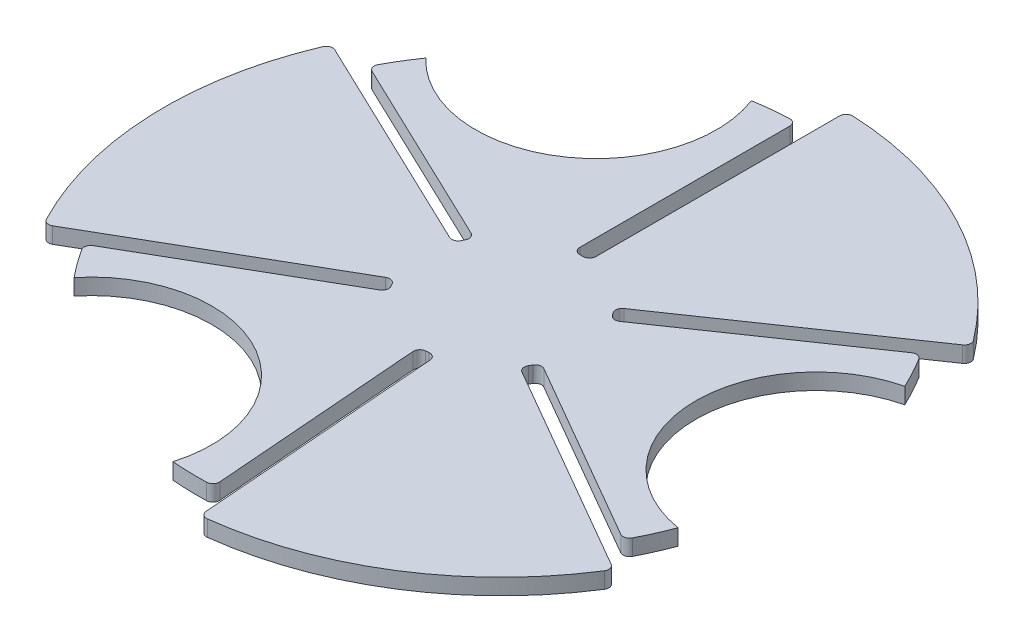
SolidWorks part; units mm, degrees
ref_plane "前基準面" through (0, 0, 0) normal (0, 0, 1) x (1, 0, 0)
ref_plane "上基準面" through (0, 0, 0) normal (0, 1, 0) x (1, 0, 0)
ref_plane "右基準面" through (0, 0, 0) normal (1, 0, 0) x (0, 0, -1)
sketch "草圖1" plane through (0, 0, 0) normal (0, 1, 0) x (1, 0, 0)
  line L2 (50.5659, -26.3075) -> (22.9006, -10.3349)
  line L8 (-2.5, 56.9451) -> (-2.5, 25)
  line L9 (-2.5, 25) -> (2.5, 25)
  line L10 (2.5, 56.9451) -> (2.5, 25)
  line L11 (22.9006, -10.3349) -> (20.4006, -14.6651)
  line L12 (48.0659, -30.6376) -> (20.4006, -14.6651)
  line L13 (-48.0659, -30.6376) -> (-20.4006, -14.6651)
  line L14 (-20.4006, -14.6651) -> (-22.9006, -10.3349)
  line L15 (-50.5659, -26.3075) -> (-22.9006, -10.3349)
  line L16 (20.6126, 14.1465) -> (0, 0) construction
  line L17 (4.4373, -24.7297) -> (6.9225, -56.5781)
  line L18 (22.0272, 12.0852) -> (48.3661, 30.1616)
  line L19 (19.1979, 16.2077) -> (45.5368, 34.2841)
  line L20 (19.1979, 16.2077) -> (22.0272, 12.0852)
  line L21 (-0.5475, -25.1187) -> (1.9377, -56.9671)
  line L22 (4.4373, -24.7297) -> (-0.5475, -25.1187)
  line L23 (-23.6352, 8.522) -> (-52.4593, 22.2939)
  line L24 (-21.4797, 13.0335) -> (-50.3038, 26.8054)
  line L25 (-23.6352, 8.522) -> (-21.4797, 13.0335)
  arc A35 (-2.5, 56.9451) -> (-50.3038, 26.8054) centre (0, 0) ccw
  circle A36 centre (0, 0) radius 25 construction
  arc A37 (50.5659, -26.3075) -> (48.3661, 30.1616) centre (0, 0) ccw
  arc A38 (-48.0659, -30.6376) -> (1.9377, -56.9671) centre (0, 0) ccw
  arc A39 (45.5368, 34.2841) -> (2.5, 56.9451) centre (0, 0) ccw
  arc A40 (-52.4593, 22.2939) -> (-50.5659, -26.3075) centre (0, 0) ccw
  arc A41 (6.9225, -56.5781) -> (48.0659, -30.6376) centre (0, 0) ccw
  point P1 (0, 25)
  dimension "D1" = 114
  dimension "D2" = 5
  dimension "D3" = 50
  dimension "D4" = 55.538
  dimension "D5" = 3
extrude "填料-伸長1" add sketch "草圖1" against normal blind 5
sketch "草圖4" plane through (0, 0, 0) normal (0, 1, 0) x (1, 0, 0)
  line L0 (48.0659, -30.6376) -> (20.4006, -14.6651) construction
  line L1 (4.4373, -24.7297) -> (6.9225, -56.5781) construction
  line L2 (48.0659, -30.6376) -> (20.4006, -14.6651) construction
  line L3 (4.4373, -24.7297) -> (6.9225, -56.5781) construction
  line L4 (6.9225, -56.5781) -> (10.6587, -104.4576)
  line L5 (48.0659, -30.6376) -> (89.6569, -54.6502)
  line L6 (-52.4593, 22.2939) -> (-95.7923, 42.9981)
  line L7 (-50.5659, -26.3075) -> (-92.1569, -50.3201)
  line L8 (45.5368, 34.2841) -> (85.1336, 61.4595)
  line L9 (2.5, 56.9451) -> (2.5, 104.9702)
  line L10 (0, 0) -> (-61.4999, -116.7979) construction
  line L11 (1.9377, -56.9671) -> (4.86, -94.4163)
  line L12 (-48.0659, -30.6376) -> (-80.5608, -49.3985)
  line L13 (-48.0659, -30.6376) -> (-20.4006, -14.6651) construction
  line L14 (-0.5475, -25.1187) -> (1.9377, -56.9671) construction
  line L15 (-50.3038, 26.8054) -> (-84.1969, 42.9993)
  line L16 (-2.5, 56.9451) -> (-2.5, 94.4669)
  line L17 (48.3661, 30.1616) -> (79.3369, 51.417)
  line L18 (50.5659, -26.3075) -> (83.0608, -45.0684)
  arc A0 (10.6587, -104.4576) -> (89.6569, -54.6502) centre (0, 0) ccw
  arc A1 (6.9225, -56.5781) -> (48.0659, -30.6376) centre (0, 0) ccw construction
  arc A2 (6.9225, -56.5781) -> (48.0659, -30.6376) centre (0, 0) ccw
  arc A3 (-95.7923, 42.9981) -> (-92.1569, -50.3201) centre (0, 0) ccw
  arc A4 (-52.4593, 22.2939) -> (-50.5659, -26.3075) centre (0, 0) ccw
  arc A5 (85.1336, 61.4595) -> (2.5, 104.9702) centre (0, 0) ccw
  arc A6 (45.5368, 34.2841) -> (2.5, 56.9451) centre (0, 0) ccw
  arc A8 (-48.0659, -30.6376) -> (1.9377, -56.9671) centre (0, 0) ccw construction
  arc A9 (-8.0402, -94.1573) -> (-73.0833, -59.9089) centre (-44.0284, -83.6167) ccw
  arc A10 (-77.5225, 54.0417) -> (-84.1596, 42.9815) centre (0, 0) ccw
  arc A11 (-77.5225, 54.0417) -> (-15.341, 93.2465) centre (-50.4, 79.938) ccw
  arc A12 (-2.5, 94.4669) -> (-15.341, 93.2465) centre (0, 0) ccw
  arc A13 (-8.0402, -94.1573) -> (4.8567, -94.3751) centre (0, 0) ccw
  arc A14 (-79.6883, -50.794) -> (3.2125, -94.4454) centre (0, 0) ccw
  arc A15 (-80.5608, -49.3985) -> (-73.0833, -59.9089) centre (0, 0) ccw
  arc A16 (85.5628, 40.1156) -> (79.3029, 51.3936) centre (0, 0) ccw
  arc A17 (85.5628, 40.1156) -> (88.4243, -33.3376) centre (94.4284, 3.6787) ccw
  arc A18 (83.0608, -45.0684) -> (88.4243, -33.3376) centre (0, 0) ccw
  arc M12 (6.9225, -56.5781) -> (48.0659, -30.6376) centre (0, 0) ccw
  arc M16 (50.5659, -26.3075) -> (48.3661, 30.1616) centre (0, 0) ccw
  arc M20 (45.5368, 34.2841) -> (2.5, 56.9451) centre (0, 0) ccw
  arc M24 (-2.5, 56.9451) -> (-50.3038, 26.8054) centre (0, 0) ccw
  arc M28 (-52.4593, 22.2939) -> (-50.5659, -26.3075) centre (0, 0) ccw
  arc M32 (-48.0659, -30.6376) -> (1.9377, -56.9671) centre (0, 0) ccw
  dimension "D1" = 210
  dimension "D3" = 37.5
  dimension "D5" = 37.5
  dimension "D2" = 3
extrude "填料-伸長2" add sketch "草圖4" against normal up to surface (5 mm away) contours L6 A3 L7 M28 | L4 A0 L5 M12 | L8 A5 L9 M20 | L12 A15 A9 M32 | A9 A13 L11 M32 | A11 A10 L15 M24 | L16 A12 A11 M24 | A17 A16 L17 M16 | L18 A18 A17 M16 up to face at (0, -5, 0)
fillet "圓角1" radius 2 24 edges at (-2.5, -2.5, -25) (2.5, -2.5, -25) (22.9006, -2.5, 10.3349) (20.4006, -2.5, 14.6651) (-20.4006, -2.5, 14.6651) (-22.9006, -2.5, 10.3349) (22.0272, -2.5, -12.0852) (19.1979, -2.5, -16.2077) (-21.4797, -2.5, -13.0335) (-23.6352, -2.5, -8.522) (4.4373, -2.5, 24.7297) (-0.5475, -2.5, 25.1187) (-92.1569, -2.5, 50.3201) (-80.5608, -2.5, 49.3985) (-84.1596, -2.5, -42.9815) (-95.7923, -2.5, -42.9981) (-2.5, -2.5, -94.4669) (2.5, -2.5, -104.9702) (85.1336, -2.5, -61.4595) (79.3029, -2.5, -51.3936) (83.0608, -2.5, 45.0684) (89.6569, -2.5, 54.6502) (10.6587, -2.5, 104.4576) (4.8567, -2.5, 94.3751)
